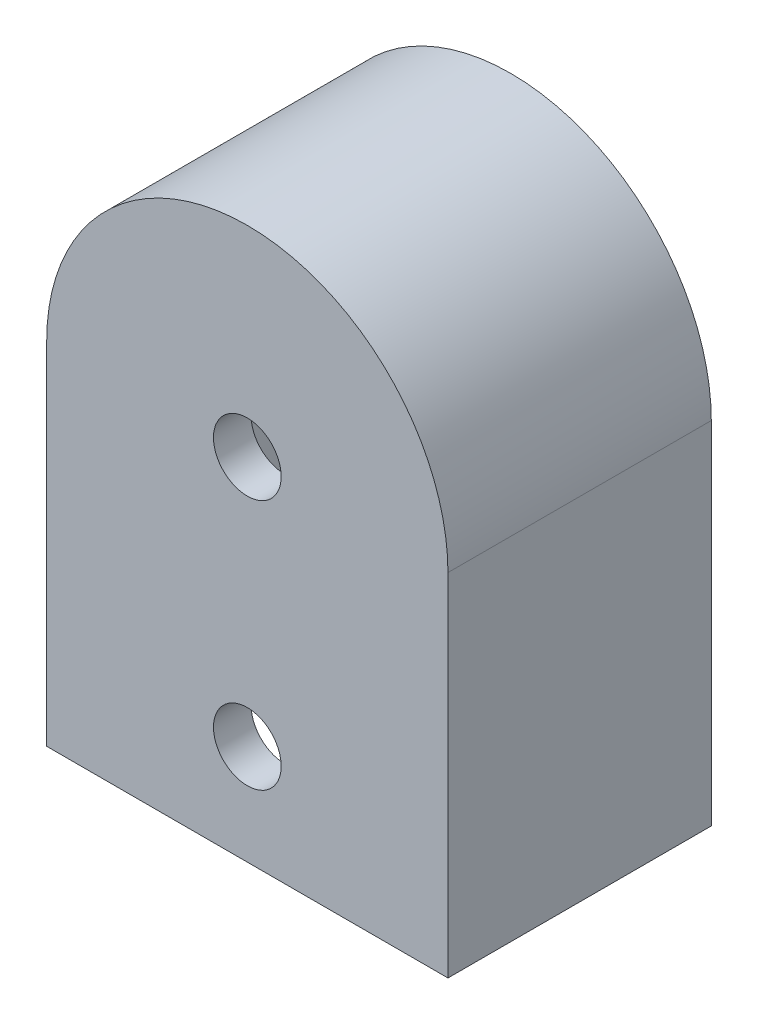
SolidWorks part; units mm, degrees
ref_plane "Front Plane" through (0, 0, 0) normal (0, 0, 1) x (1, 0, 0)
ref_plane "Top Plane" through (0, 0, 0) normal (0, 1, 0) x (1, 0, 0)
ref_plane "Right Plane" through (0, 0, 0) normal (1, 0, 0) x (0, 0, -1)
sketch "Sketch2" plane through (0, 0, 0) normal (0, 0, 1) x (1, 0, 0)
  line L0 (-20.32, 0.0264) -> (20.32, 0.0264)
  arc A0 (20.32, 0.0264) -> (-20.32, 0.0264) centre (0, 0) ccw
  dimension "D1" = 20.32
extrude "Boss-Extrude1" add sketch "Sketch2" along normal blind 26.67
sketch "Sketch3" plane through (0, 0.0264, 0) normal (0, -1, 0) x (-1, 0, 0)
  line L1 (20.32, -26.67) -> (-20.32, -26.67)
  line L2 (20.32, -26.67) -> (20.32, 0)
  line L3 (20.32, 0) -> (-20.32, 0)
  line L4 (-20.32, -26.67) -> (-20.32, 0)
extrude "Boss-Extrude2" add sketch "Sketch3" along normal blind 35.56
sketch "Sketch8" plane through (0, 0, 0) normal (0, 0, 1) x (1, 0, 0)
  line L0 (15.24, 0) -> (-15.24, 0)
  arc A0 (15.24, 0) -> (-15.24, 0) centre (0, 0) ccw
extrude "Cut-Extrude3" cut sketch "Sketch8" along normal blind 19.05 from offset 3.81
sketch "Sketch9" plane through (0, 0, 0) normal (0, 1, 0) x (1, 0, 0)
  line L1 (15.24, -22.86) -> (-15.24, -22.86)
  line L2 (15.24, -22.86) -> (15.24, -3.81)
  line L3 (15.24, -3.81) -> (-15.24, -3.81)
  line L4 (-15.24, -22.86) -> (-15.24, -3.81)
extrude "Cut-Extrude4" cut sketch "Sketch9" against normal up to surface (35.5336 mm away) up to face at (0, -35.5336, 13.335)
sketch "Sketch10" plane through (0, 0, 0) normal (0, 0, 1) x (1, 0, 0)
  circle A0 centre (0, 0) radius 3.429
extrude "Cut-Extrude8" cut sketch "Sketch10" along normal up to surface (26.67 mm away) up to face at (0, -12.6802, 26.67)
sketch "Sketch11" plane through (0, 0, 0) normal (0, 0, 1) x (1, 0, 0)
  circle A0 centre (12.7, 0) radius 5.715
  dimension "D1" = 12.7
sketch "Sketch12" plane through (0, 0, 0) normal (0, 0, 1) x (1, 0, 0)
  circle A0 centre (12.7, -25.4) radius 5.715
  dimension "D1" = 25.4
extrude "Cut-Extrude9" cut sketch "Sketch11" along normal blind 3.048
extrude "Cut-Extrude10" cut sketch "Sketch12" along normal blind 3.048
sketch "Sketch13" plane through (0, 0, 0) normal (0, 0, -1) x (-1, 0, 0)
  circle A0 centre (12.7, 0) radius 5.715
  circle A1 centre (12.7, -25.4) radius 5.715
  dimension "D1" = 12.7
  dimension "D2" = 25.4
extrude "Cut-Extrude11" cut sketch "Sketch13" against normal blind 3.048
sketch "Sketch16" plane through (0, 0, 0) normal (0, 0, -1) x (-1, 0, 0)
  circle A0 centre (0, -25.4) radius 3.429
  dimension "D1" = 25.4
extrude "Cut-Extrude12" cut sketch "Sketch16" against normal through all both and the other way through all
